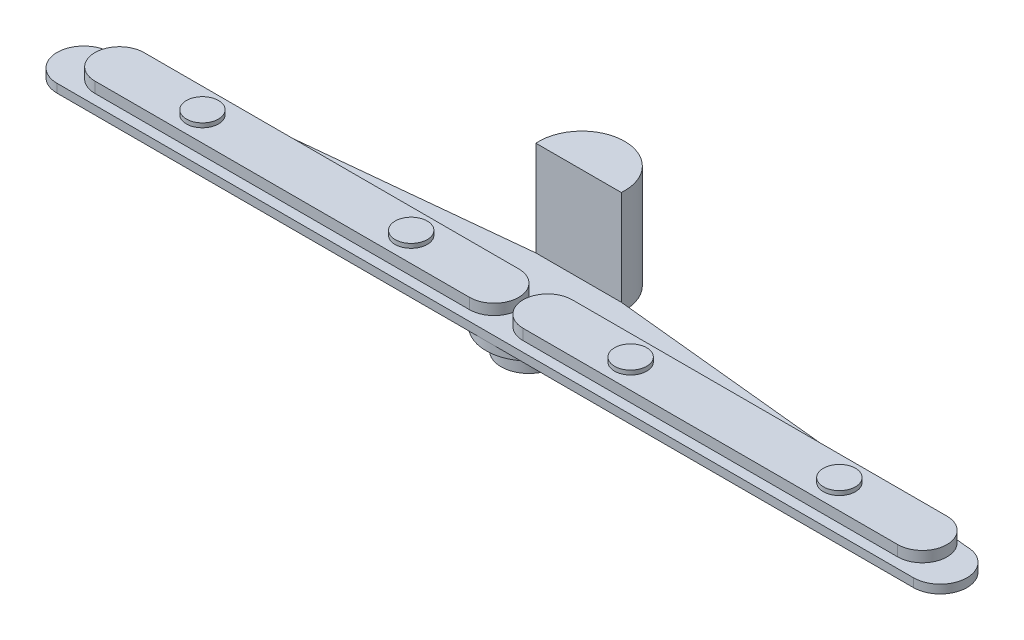
SolidWorks part; units mm, degrees
material "Ductile Iron"
ref_plane "Front Plane" through (0, 0, 0) normal (0, 0, 1) x (1, 0, 0)
ref_plane "Top Plane" through (0, 0, 0) normal (0, 1, 0) x (1, 0, 0)
ref_plane "Right Plane" through (0, 0, 0) normal (1, 0, 0) x (0, 0, -1)
sketch "Sketch1" plane through (0, 0, 0) normal (0, 1, 0) x (1, 0, 0)
  line L2 (-1446.8954, -407.2331) -> (2553.1046, -407.2331) construction
  line L5 (-1446.8954, -532.2331) -> (2553.1046, -532.2331)
  line L6 (-1438.6392, -282.5061) -> (357.7568, -100.2293)
  line L7 (2553.0605, -282.2331) -> (756.6368, -100.2293)
  arc A8 (756.6368, -100.2293) -> (357.7568, -100.2293) centre (557.1968, -85.2731) ccw
  arc A9 (2553.1046, -532.2331) -> (2553.0605, -282.2331) centre (2553.1046, -407.2331) ccw
  arc A10 (-1438.6392, -282.5061) -> (-1446.8954, -532.2331) centre (-1446.8954, -407.2331) ccw
  dimension "D4" = 4000
  dimension "D5" = 1805.62
  dimension "D6" = 1805.62
  dimension "D8" = 400
  dimension "D1" = 446.96
  dimension "D2" = 250
  dimension "D9" = 250
  dimension "D3" = 4000
  dimension "D7" = 398.88
extrude "Boss-Extrude1" add sketch "Sketch1" along normal blind 40
sketch "Sketch2" plane through (0, 40, 0) normal (0, 1, 0) x (1, 0, 0)
  line L0 (-1317.8032, -369.7331) -> (432.1968, -369.7331) construction
  line L1 (682.1968, -369.7331) -> (2432.1968, -369.7331) construction
  line L2 (-1446.8954, -532.2331) -> (2553.1046, -532.2331) construction
  line L3 (557.1968, 114.7269) -> (557.1968, -532.2331) construction
  line L4 (682.1968, -254.7331) -> (2432.1968, -254.7331)
  line L5 (682.1968, -484.7331) -> (2432.1968, -484.7331)
  line L6 (432.1968, -484.7331) -> (-1317.8032, -484.7331)
  line L7 (357.7568, -100.2293) -> (756.6368, -100.2293) construction
  line L8 (-1317.8032, -254.7331) -> (432.1968, -254.7331)
  arc A0 (2432.1968, -484.7331) -> (2432.1968, -254.7331) centre (2432.1968, -369.7331) ccw
  arc A1 (682.1968, -254.7331) -> (682.1968, -484.7331) centre (682.1968, -369.7331) ccw
  arc A2 (432.1968, -484.7331) -> (432.1968, -254.7331) centre (432.1968, -369.7331) ccw
  arc A3 (-1317.8032, -254.7331) -> (-1317.8032, -484.7331) centre (-1317.8032, -369.7331) ccw
  point P6 (557.1968, -208.7531)
  dimension "D1" = 230
  dimension "D2" = 1750
  dimension "D3" = 1750
  dimension "D4" = 162.5
  dimension "D5" = 250
  dimension "D6" = 125
  dimension "D7" = 1750
  dimension "D8" = 1750
extrude "Boss-Extrude2" add sketch "Sketch2" along normal blind 50
sketch "Sketch3" plane through (0, 90, 0) normal (0, 1, 0) x (1, 0, 0)
  line L0 (357.7568, -100.2293) -> (756.6368, -100.2293) construction
  line L1 (-930.3032, -369.7331) -> (44.6968, -369.7331) construction
  line L2 (44.6968, -369.7331) -> (1069.6968, -369.7331) construction
  line L3 (1069.6968, -369.7331) -> (2044.6968, -369.7331) construction
  line L4 (557.1968, 114.7269) -> (557.1968, -369.7331) construction
  line L6 (2432.1968, -254.7331) -> (682.1968, -254.7331) construction
  circle A0 centre (-930.3032, -369.7331) radius 75
  circle A1 centre (44.6968, -369.7331) radius 75
  circle A2 centre (1069.6968, -369.7331) radius 75
  circle A3 centre (2044.6968, -369.7331) radius 75
  point P14 (557.1968, -100.2293)
  dimension "D1" = 150
  dimension "D2" = 975
  dimension "D3" = 975
  dimension "D4" = 1025
  dimension "D5" = 512.5
  dimension "D6" = 115
extrude "Boss-Extrude3" add sketch "Sketch3" along normal blind 20
sketch "Sketch4" plane through (0, 0, 0) normal (0, -1, 0) x (-1, 0, 0)
  line L0 (-557.1968, 114.7269) -> (-557.1968, -532.2331) construction
  line L1 (1446.8954, -532.2331) -> (-2553.1046, -532.2331) construction
  circle A1 centre (-557.1968, -332.2331) radius 200
  dimension "D1" = 400
  dimension "D2" = 200
extrude "Boss-Extrude4" add sketch "Sketch4" along normal blind 40
sketch "Sketch5" plane through (0, 40, 0) normal (0, 1, 0) x (1, 0, 0)
  line L0 (756.6368, -100.2293) -> (357.7568, -100.2293)
  line L1 (357.7568, -100.2293) -> (-1164.9279, -254.7331) construction
  arc A0 (756.6368, -100.2293) -> (357.7568, -100.2293) centre (557.1968, -85.2731) ccw
extrude "Boss-Extrude5" add sketch "Sketch5" along normal blind 444
sketch "Sketch6" plane through (0, -40, 0) normal (0, -1, 0) x (1, 0, 0)
  circle A0 centre (557.1968, 332.2331) radius 130
extrude "Boss-Extrude6" add sketch "Sketch6" along normal blind 100
